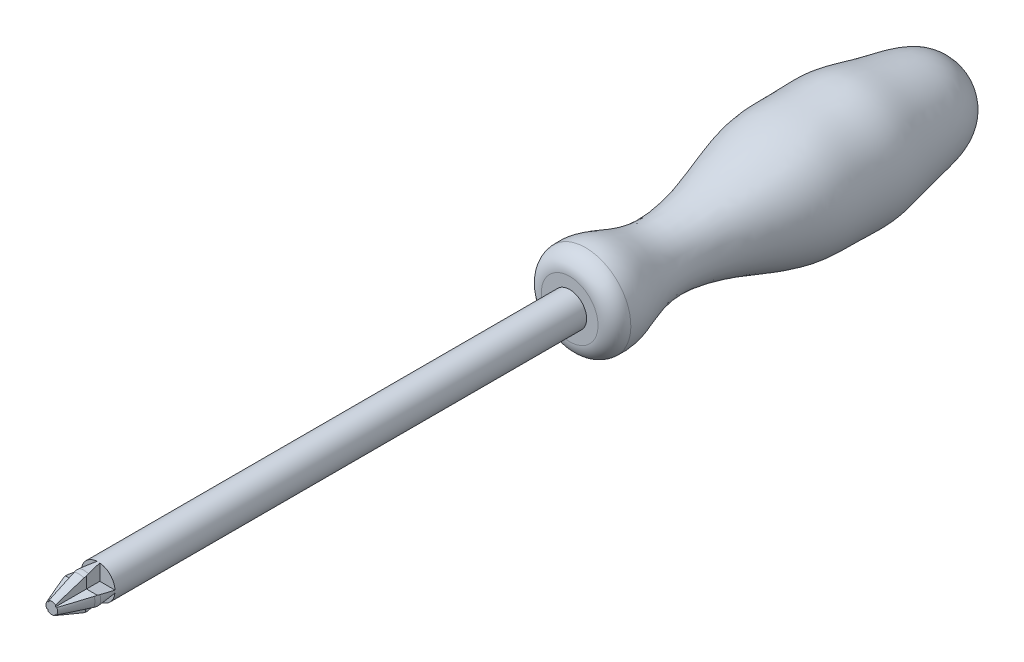
SolidWorks part; units mm, degrees
ref_plane "前基準面" through (0, 0, 0) normal (0, 0, 1) x (1, 0, 0)
ref_plane "上基準面" through (0, 0, 0) normal (0, 1, 0) x (1, 0, 0)
ref_plane "右基準面" through (0, 0, 0) normal (1, 0, 0) x (0, 0, -1)
sketch "草圖1" plane through (0, 0, 0) normal (1, 0, 0) x (0, 0, -1)
  line L0 (95.8333, 69) -> (479.1667, 69) construction
  line L1 (5.1791, 67.8085) -> (602.9228, 67.8085) construction
  line L2 (326.7064, 93.1131) -> (326.7064, 67.8085)
  line L3 (555.4174, 67.8085) -> (326.7064, 67.8085)
  spline S0 degree 3 poles (555.4174, 67.8085) (557.3711, 76.8775) (548.2594, 91.3944) (527.503, 96.4263) (510.0637, 99.6797) (491.8918, 104.4948) (472.6779, 103.2855) (446.0442, 103.9565) (412.616, 90.5494) (374.1811, 81.6395) (346.3399, 95.8062) (332.8069, 94.5026) (326.7064, 93.1131) knots 0 0 0 0 0.077127 0.13312 0.186568 0.238111 0.300462 0.358626 0.475509 0.623438 0.690891 0.744475 0.744475 0.744475 0.744475
revolve "旋轉4" add sketch "草圖1" angle 360 about L3
sketch "草圖2" plane through (0, 0, -326.7064) normal (0, 0, 1) x (1, 0, 0)
  line L0 (0, 67.8085) -> (0, 107.3522) construction
  circle A2 centre (0, 67.8085) radius 10
  circle A3 centre (0, 67.8085) radius 25.3046 construction
  point P0 (0, 63.6265)
  dimension "D1" = 20
extrude "填料-伸長1" add sketch "草圖2" along normal blind 271.27
sketch "草圖3" plane through (0, 0, 0) normal (1, 0, 0) x (0, 0, -1)
  line L0 (55.4364, 67.8085) -> (20.7764, 67.8085)
  line L1 (55.4364, 77.8085) -> (55.4364, 57.8085) construction
  line L2 (55.4364, 77.8085) -> (38.0969, 77.8085)
  line L5 (55.4364, 77.8085) -> (55.4364, 67.8085)
  line L6 (38.0969, 77.8085) -> (20.7764, 71.245)
  line L7 (20.7764, 71.245) -> (20.7764, 67.8085)
  dimension "D1" = 34.66
revolve "旋轉5" add sketch "草圖3" angle 360 about L0
fillet "圓角3" radius 8 1 edges at (-10, 67.8085, -38.0969)
sketch "草圖5" plane through (0, 0, -20.7764) normal (0, 0, 1) x (1, 0, 0)
  line L8 (2.2431, 69.568) -> (13.103, 69.568)
  line L9 (2.2431, 69.568) -> (2.2431, 80.8013)
  line L10 (2.2431, 80.8013) -> (13.103, 80.8013)
  line L11 (13.103, 69.568) -> (13.103, 80.8013)
extrude "除料-伸長1" cut sketch "草圖5" against normal blind 17.32 draft 3
pattern_circular "環狀複製排列2" count 4 over 360 about axis through (-0.0225, 67.7899, 0) along (0, 0, 1) of "除料-伸長1"
sketch "草圖6" plane through (0, 0, -38.0964) normal (0, 0, 1) x (1, 0, 0)
  line L0 (3.1508, 70.4757) -> (3.1508, 79.5448)
  line L1 (3.1508, 79.5448) -> (12.22, 70.4757)
  line L2 (12.22, 70.4757) -> (3.1508, 70.4757)
extrude "除料-伸長2" cut sketch "草圖6" against normal blind 10 draft 12 draft outward yes
pattern_circular "環狀複製排列3" count 4 over 360 about axis through (-0.0038, 67.8054, 0) along (0, 0, 1) of "除料-伸長2"
fillet "圓角5" radius 10 1 edges at (-25.3046, 67.8085, -326.7064)
